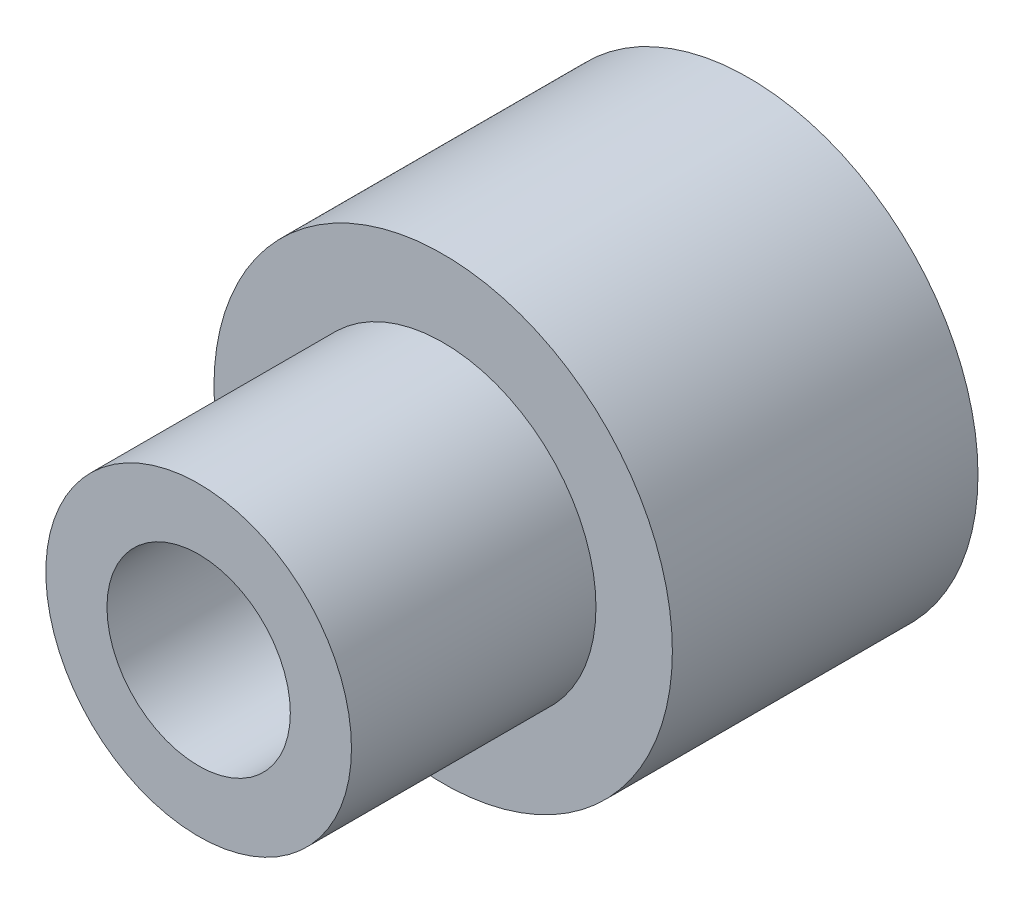
SolidWorks part; units mm, degrees
ref_plane "前视基准面" through (0, 0, 0) normal (0, 0, 1) x (1, 0, 0)
ref_plane "上视基准面" through (0, 0, 0) normal (0, 1, 0) x (1, 0, 0)
ref_plane "右视基准面" through (0, 0, 0) normal (1, 0, 0) x (0, 0, -1)
sketch "草图1" plane through (0, 0, 0) normal (0, 0, 1) x (1, 0, 0)
  circle A0 centre (0, 0) radius 7.5
  dimension "D1" = 15
extrude "凸台-拉伸1" add sketch "草图1" along normal blind 10
sketch "草图2" plane through (0, 0, 10) normal (0, 0, 1) x (1, 0, 0)
  circle A0 centre (0, 0) radius 3
  circle A1 centre (0, 0) radius 5
  dimension "D1" = 10
  dimension "D2" = 6
extrude "凸台-拉伸2" add sketch "草图2" along normal blind 8
